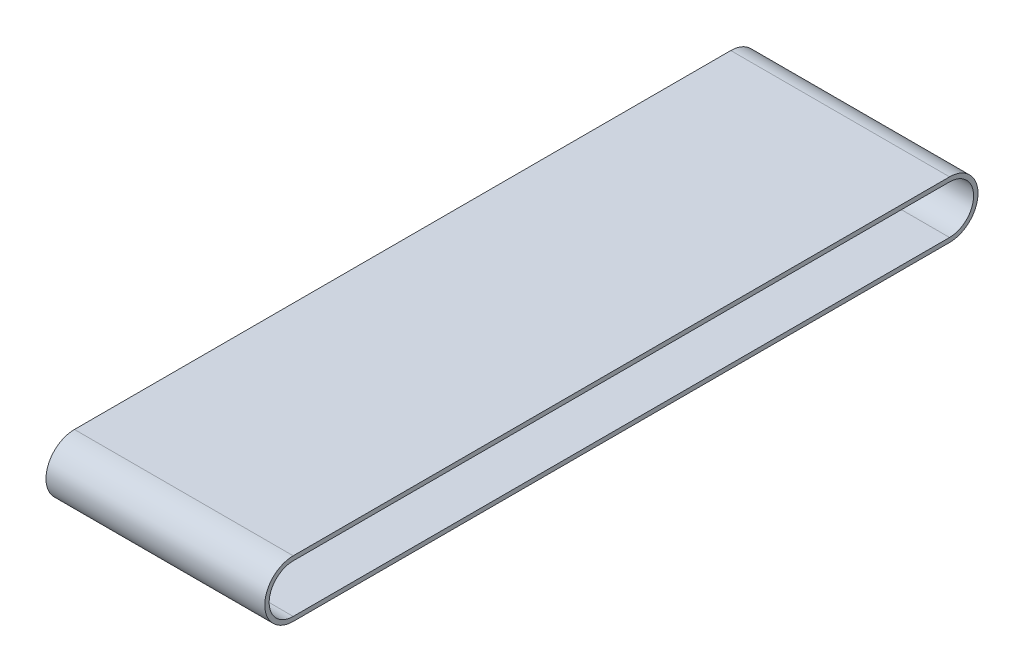
SolidWorks part; units mm, degrees
ref_plane "Front Plane" through (0, 0, 0) normal (0, 0, 1) x (1, 0, 0)
ref_plane "Top Plane" through (0, 0, 0) normal (0, 1, 0) x (1, 0, 0)
ref_plane "Right Plane" through (0, 0, 0) normal (1, 0, 0) x (0, 0, -1)
sketch "Sketch1" plane through (0, 0, 0) normal (1, 0, 0) x (0, 0, -1)
  line L0 (-183.6787, 35.8481) -> (116.3213, 35.8481)
  line L1 (-183.6787, 35.8481) -> (-183.6787, 9.8481) construction
  line L2 (-33.6787, 35.8481) -> (-33.6787, -19.5304) construction
  line L3 (-183.6787, 9.8481) -> (116.3213, 9.8481)
  line L4 (-183.6787, 11.8481) -> (116.3213, 11.8481)
  line L5 (-183.6787, 33.8481) -> (116.3213, 33.8481)
  arc A0 (-183.6787, 35.8481) -> (-183.6787, 9.8481) centre (-183.6787, 22.8481) ccw
  arc A1 (116.3213, 35.8481) -> (116.3213, 9.8481) centre (116.3213, 22.8481) cw
  arc A2 (-183.6787, 33.8481) -> (-183.6787, 11.8481) centre (-183.6787, 22.8481) ccw
  arc A3 (116.3213, 33.8481) -> (116.3213, 11.8481) centre (116.3213, 22.8481) cw
  dimension "D1" = 300
  dimension "D2" = 26
  dimension "D3" = 2
extrude "Boss-Extrude1" add sketch "Sketch1" along normal blind 100
